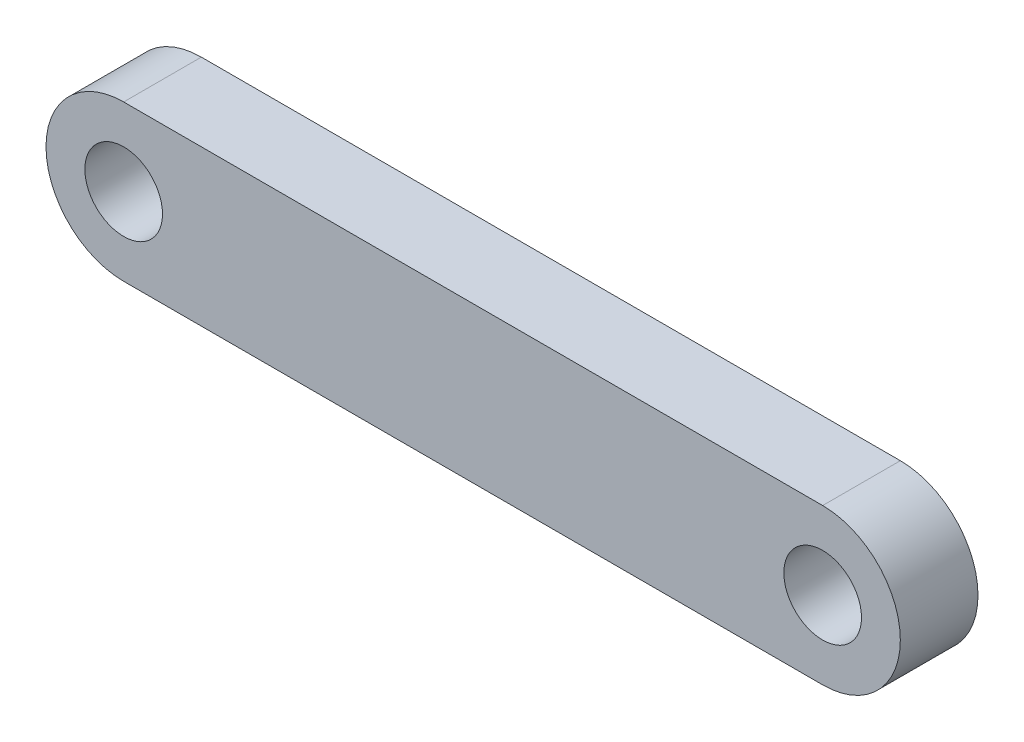
SolidWorks part; units mm, degrees
ref_plane "Front Plane" through (0, 0, 0) normal (0, 0, 1) x (1, 0, 0)
ref_plane "Top Plane" through (0, 0, 0) normal (0, 1, 0) x (1, 0, 0)
ref_plane "Right Plane" through (0, 0, 0) normal (1, 0, 0) x (0, 0, -1)
sketch "Sketch1" plane through (0, 0, 0) normal (0, 0, 1) x (1, 0, 0)
  line L0 (-59.9967, 24.6341) -> (-104.9967, 24.6341) construction
  line L1 (-59.9967, 19.6341) -> (-104.9967, 19.6341)
  line L2 (-59.9967, 29.6341) -> (-104.9967, 29.6341)
  circle A0 centre (-59.9967, 24.6341) radius 2.5
  arc A1 (-59.9967, 19.6341) -> (-59.9967, 29.6341) centre (-59.9967, 24.6341) ccw
  arc A2 (-104.9967, 29.6341) -> (-104.9967, 19.6341) centre (-104.9967, 24.6341) ccw
  circle A3 centre (-104.9967, 24.6341) radius 2.5
  point P3 (-82.4967, 24.6341)
  dimension "D2" = 5
  dimension "D4" = 5
  dimension "D1" = 10
  dimension "D3" = 45
extrude "Boss-Extrude1" add sketch "Sketch1" against normal blind 5
